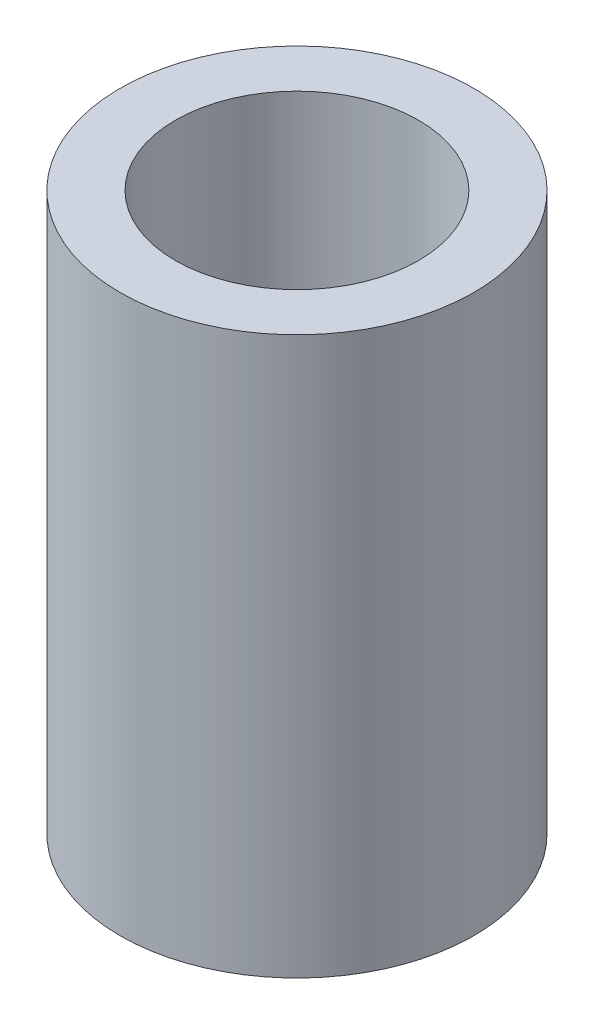
SolidWorks part; units mm, degrees
ref_plane "Front Plane" through (0, 0, 0) normal (0, 0, 1) x (1, 0, 0)
ref_plane "Top Plane" through (0, 0, 0) normal (0, 1, 0) x (1, 0, 0)
ref_plane "Right Plane" through (0, 0, 0) normal (1, 0, 0) x (0, 0, -1)
sketch "Sketch1" plane through (0, 0, 0) normal (0, 1, 0) x (1, 0, 0)
  circle A0 centre (0, 0) radius 2.75
  circle A1 centre (0, 0) radius 4
  dimension "D1" = 5.5
  dimension "D2" = 8
extrude "Boss-Extrude1" add sketch "Sketch1" along normal blind 12.6
